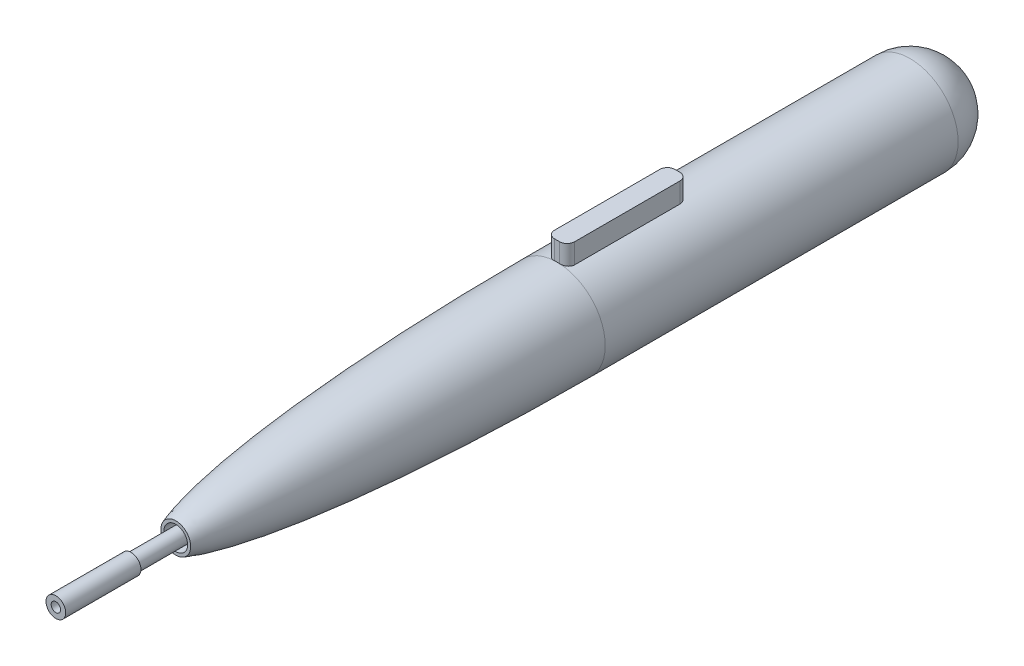
SolidWorks part; units mm, degrees
ref_plane "Front Plane" through (0, 0, 0) normal (0, 0, 1) x (1, 0, 0)
ref_plane "Top Plane" through (0, 0, 0) normal (0, 1, 0) x (1, 0, 0)
ref_plane "Right Plane" through (0, 0, 0) normal (1, 0, 0) x (0, 0, -1)
sketch "Sketch1" plane through (0, 0, 0) normal (1, 0, 0) x (0, 0, -1)
  line L4 (-966.2067, 37.7) -> (-966.2067, 25)
  line L5 (-966.2067, 25) -> (0, 25)
  line L6 (0, 25) -> (0, 0)
  line L7 (0, 121.92) -> (894.08, 121.92)
  line L8 (0, 0) -> (1016, 0)
  arc A1 (894.08, 121.92) -> (1016, 0) centre (894.08, 0) cw
  ellipse E0 centre (0, 0) end of major axis (1016, 0) minor radius 121.92 (0, 121.92) -> (-966.2067, 37.7) ccw
  dimension "D1" = 25
  dimension "D2" = 12.7
  dimension "D3" = 2032
  dimension "D4" = 121.92
  dimension "D5" = 1016
revolve "Revolve1" add sketch "Sketch1" angle 360 about L8
sketch "Sketch2" plane through (0, 0, 0) normal (0, 0, 1) x (1, 0, 0)
  circle A0 centre (0, 0) radius 30
  dimension "D2" = 60
extrude "Cut-Extrude1" cut sketch "Sketch2" along normal through all
sketch "Sketch3" plane through (0, 0, 0) normal (0, 0, 1) x (1, 0, 0)
  circle A0 centre (0, 0) radius 25
  dimension "D1" = 50
extrude "Boss-Extrude1" add sketch "Sketch3" along normal blind 1270
sketch "Sketch4" plane through (0, 0, 1270) normal (0, 0, 1) x (1, 0, 0)
  circle A0 centre (0, 0) radius 12
  dimension "D1" = 24
extrude "Cut-Extrude2" cut sketch "Sketch4" against normal blind 1103.63
ref_plane "Plane1" through (0, 0, 1079.5) normal (0, 0, 1) x (1, 0, 0)
sketch "Sketch5" plane through (0, 0, 1079.5) normal (0, 0, 1) x (1, 0, 0)
  circle A0 centre (0, 0) radius 25 construction
  circle A1 centre (0, 0) radius 25
  circle A3 centre (0, 0) radius 20
  dimension "D1" = 40
extrude "Cut-Extrude3" cut sketch "Sketch5" against normal blind 1016
sketch "Sketch6" plane through (0, 0, 0) normal (0, 0, 1) x (1, 0, 0)
  line L0 (-25.4, 170.0448) -> (25.4, 170.0448)
  line L1 (25.4, 170.0448) -> (25.4, 119.2448)
  line L2 (-25.4, 170.0448) -> (-25.4, 119.2448)
  circle A0 centre (0, 0) radius 121.92 construction
  arc A1 (25.4, 119.2448) -> (-25.4, 119.2448) centre (0, 0) ccw
  point P2 (0, 170.0448)
  dimension "D1" = 50.8
  dimension "D2" = 50.8
extrude "Boss-Extrude2" add sketch "Sketch6" against normal blind 304.8
fillet "Fillet1" radius 19.05 4 edges at (-25.4, 144.6448, -304.8) (25.4, 144.6448, -304.8) (-25.4, 144.6448, 0) (25.4, 144.6448, 0)
equation "\"D5@Sketch1\"=\"D3@Sketch1\"*1/2"
